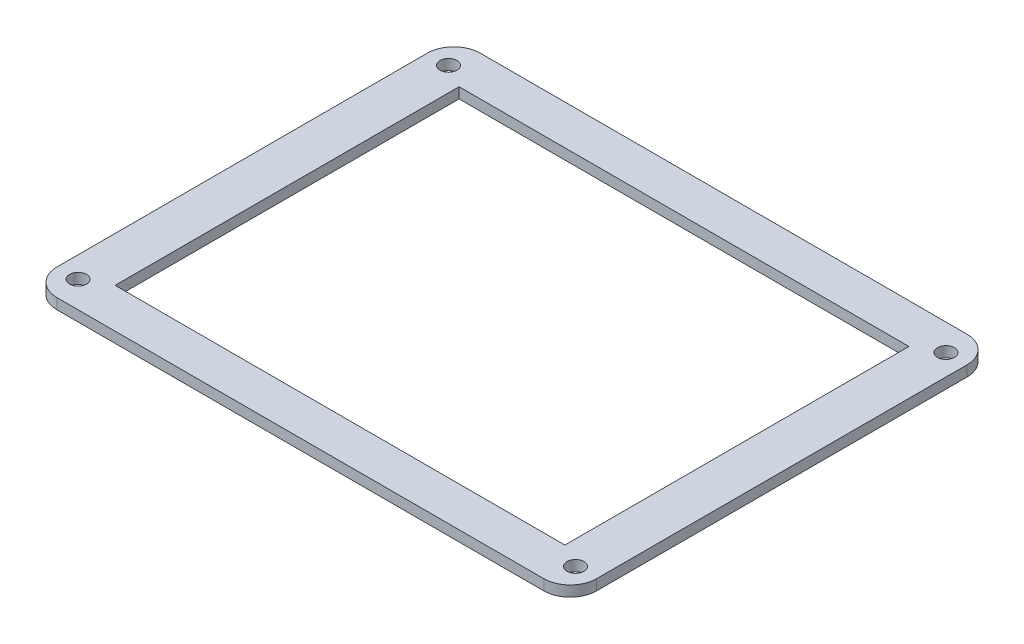
SolidWorks part; units mm, degrees
ref_plane "Front Plane" through (0, 0, 0) normal (0, 0, 1) x (1, 0, 0)
ref_plane "Top Plane" through (0, 0, 0) normal (0, 1, 0) x (1, 0, 0)
ref_plane "Right Plane" through (0, 0, 0) normal (1, 0, 0) x (0, 0, -1)
sketch "Sketch1" plane through (0, 0, 0) normal (0, 1, 0) x (1, 0, 0)
  line L1 (-51, 40) -> (51, 40)
  line L2 (-51, 40) -> (-51, -40)
  line L3 (-51, -40) -> (51, -40)
  line L4 (51, 40) -> (51, -40)
  line L5 (-51, 40) -> (51, -40) construction
  line L6 (-51, -40) -> (51, 40) construction
  line L7 (-42.5, 32.5) -> (42.5, 32.5)
  line L8 (-42.5, 32.5) -> (-42.5, -32.5)
  line L9 (-42.5, -32.5) -> (42.5, -32.5)
  line L10 (42.5, 32.5) -> (42.5, -32.5)
  line L11 (-42.5, 32.5) -> (42.5, -32.5) construction
  line L12 (-42.5, -32.5) -> (42.5, 32.5) construction
  circle A0 centre (47, 35) radius 1.6 construction
  circle A1 centre (47, -35) radius 1.6 construction
  circle A2 centre (-47, -35) radius 1.6 construction
  circle A3 centre (-47, 35) radius 1.6 construction
  circle A4 centre (47, 35) radius 1.6
  circle A5 centre (47, -35) radius 1.6
  circle A6 centre (-47, -35) radius 1.6
  circle A7 centre (-47, 35) radius 1.6
  point P0 (0, 0)
  point P6 (0, 0)
  dimension "D1" = 65
  dimension "D2" = 85
  dimension "D3" = 102
  dimension "D4" = 80
extrude "Boss-Extrude1" add sketch "Sketch1" along normal blind 2 contours L2 L1 L4 L3 | L8 L7 L10 L9
fillet "Fillet2" radius 5 4 edges at (-51, 1, -40) (-51, 1, 40) (51, 1, 40) (51, 1, -40)
sketch "Sketch2" plane through (0, 2, 0) normal (0, 1, 0) x (1, 0, 0)
  circle A0 centre (-47, -35) radius 1.6 construction
  circle A1 centre (47, -35) radius 1.6 construction
  circle A2 centre (47, 35) radius 1.6 construction
  circle A3 centre (-47, 35) radius 1.6 construction
  circle A4 centre (-47, -35) radius 1.6
  circle A5 centre (47, -35) radius 1.6
  circle A6 centre (47, 35) radius 1.6
  circle A7 centre (-47, 35) radius 1.6
extrude "Cut-Extrude1" cut sketch "Sketch2" against normal mid plane 129
